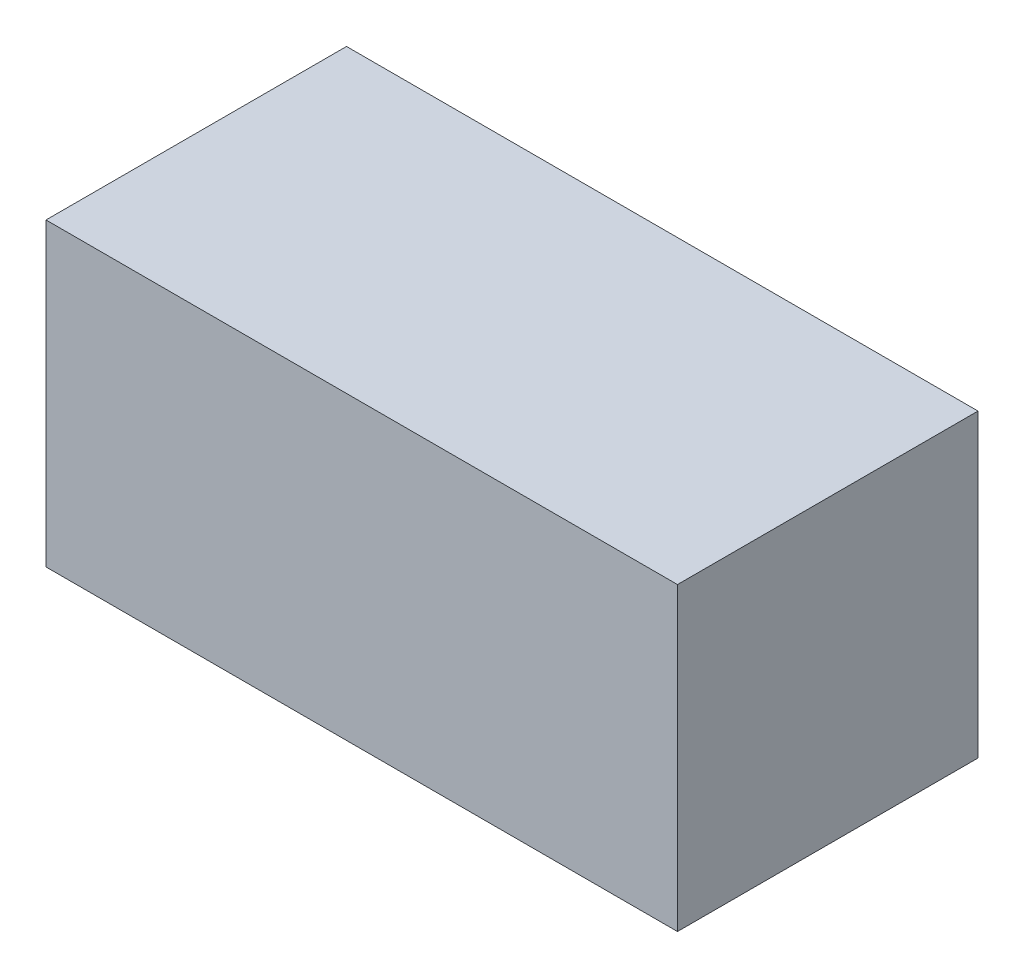
SolidWorks part; units mm, degrees
ref_plane "Front Plane" through (0, 0, 0) normal (0, 0, 1) x (1, 0, 0)
ref_plane "Top Plane" through (0, 0, 0) normal (0, 1, 0) x (1, 0, 0)
ref_plane "Right Plane" through (0, 0, 0) normal (1, 0, 0) x (0, 0, -1)
sketch "Sketch2" plane through (0, 0, 0) normal (1, 0, 0) x (0, 0, -1)
  line L0 (-2.3812, -2.3813) -> (2.3813, 2.3813) construction
  line L1 (-2.3813, 2.3813) -> (2.3813, 2.3813) construction
  line L2 (-2.3813, 2.3813) -> (-2.3812, -2.3813) construction
  line L3 (-2.3812, -2.3813) -> (2.3813, -2.3813) construction
  line L4 (2.3813, 2.3813) -> (2.3813, -2.3813) construction
  dimension "Height" = 4.7625
  dimension "Width" = 4.7625
sketch "Sketch1" plane through (0, 0, 0) normal (0, 0, 1) x (1, 0, 0)
  line L0 (-6.35, 0) -> (6.35, 0) construction
  line L1 (-6.35, 2.3813) -> (6.35, 2.3813) construction
  point P8 (0, 0)
  dimension "Length" = 12.7
sketch "Sketch3" plane through (0, 0, 0) normal (0, 1, 0) x (1, 0, 0)
  line L1 (-5.0038, 2.3813) -> (5.0038, 2.3813)
  line L2 (-5.0038, 2.3813) -> (-5.0038, -2.3812)
  line L3 (-5.0038, -2.3812) -> (5.0038, -2.3812)
  line L4 (5.0038, 2.3813) -> (5.0038, -2.3812)
  dimension "D1" = 10.0076
extrude "Extrude1" add sketch "Sketch3" against normal up to vertex (2.3813 mm away) and the other way up to vertex (2.3813 mm away)
sketch "Sketch5" plane through (0, 0, 0) normal (0, 0, 1) x (1, 0, 0)
  line L0 (6.35, 0) -> (2.1167, 0) construction
  line L1 (2.1167, 0) -> (-2.1167, 0) construction
  line L2 (-2.1167, 0) -> (2.1167, 0) construction
  line L3 (2.1167, 0) -> (-2.1167, 0) construction
  line L4 (-2.1167, 0) -> (-6.35, 0) construction
  point P2 (-4.2333, 0)
  point P7 (0, 0)
  point P8 (4.2333, 0)
  point P9 (-2.1167, 0)
  point P10 (-6.35, 0)
  point P11 (2.1167, 0)
  point P13 (6.35, 0)
sketch "Sketch6" plane through (0, 0, 2.3812) normal (0, 0, 1) x (1, 0, 0)
  line L1 (-2.1167, 0) -> (-6.35, 0) construction
  line L2 (2.1167, 0) -> (-2.1167, 0) construction
  line L3 (6.35, 0) -> (2.1167, 0) construction
  point P0 (-4.2333, 0)
  point P1 (-2.1167, 0)
  point P4 (0, 0)
  point P5 (2.1167, 0)
  point P6 (4.2333, 0)
ref_plane "Plane1" through (-4.9962, 0, 0) normal (1, 0, 0) x (0, 0, -1)
